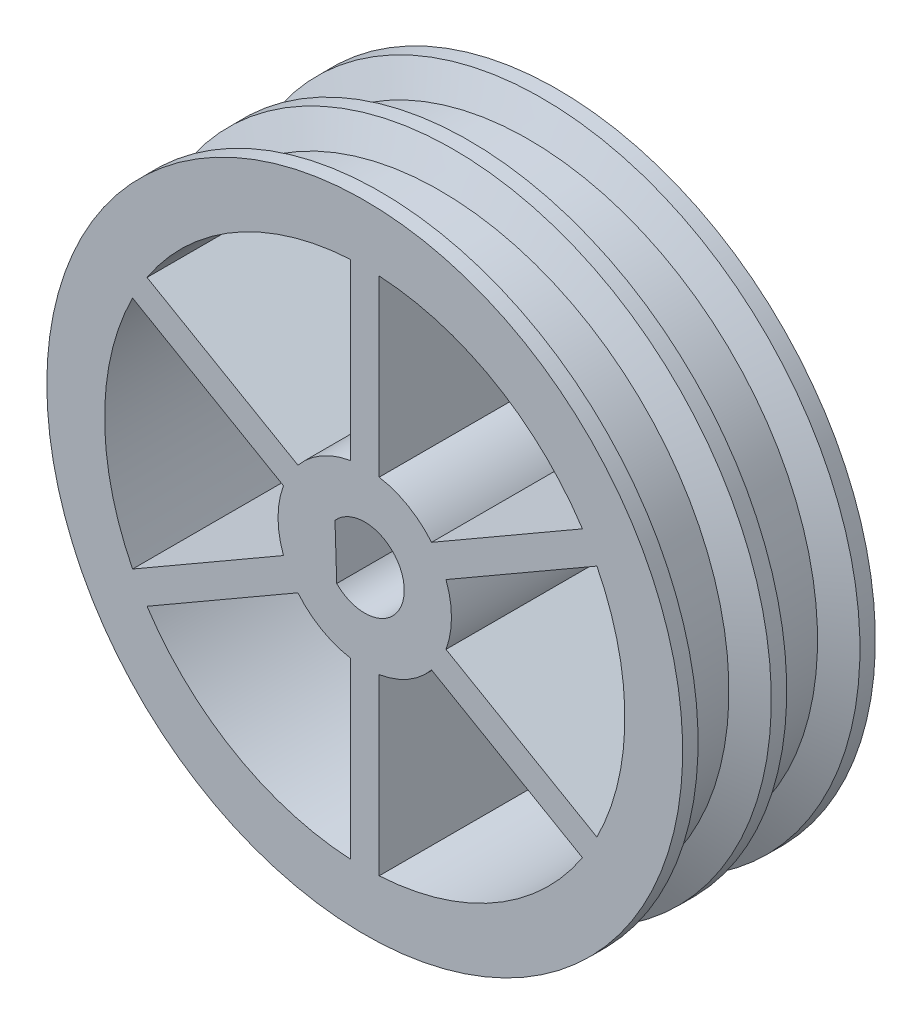
SolidWorks part; units mm, degrees
ref_plane "前视基准面" through (0, 0, 0) normal (0, 0, 1) x (1, 0, 0)
ref_plane "上视基准面" through (0, 0, 0) normal (0, 1, 0) x (1, 0, 0)
ref_plane "右视基准面" through (0, 0, 0) normal (1, 0, 0) x (0, 0, -1)
sketch "草图1" plane through (0, 0, 0) normal (0, 0, 1) x (1, 0, 0)
  line L0 (-3.0886, 2.6963) -> (-2.9082, -2.89)
  line L1 (0, 0) -> (0, 50000) construction
  line L2 (22.5966, 14.7782) -> (6.9352, 5.7361)
  line L4 (-1.5, 26.9583) -> (-1.5, 8.8741)
  line L6 (1.5, 26.9583) -> (1.5, 8.8741)
  line L7 (24.0966, 12.1801) -> (8.4352, 3.138)
  line L8 (24.0966, -12.1801) -> (8.4352, -3.138)
  line L9 (22.5966, -14.7782) -> (6.9352, -5.7361)
  line L10 (1.5, -26.9583) -> (1.5, -8.8741)
  line L11 (-1.5, -26.9583) -> (-1.5, -8.8741)
  line L12 (-22.5966, -14.7782) -> (-6.9352, -5.7361)
  line L13 (-24.0966, -12.1801) -> (-8.4352, -3.138)
  line L14 (-24.0966, 12.1801) -> (-8.4352, 3.138)
  line L15 (-22.5966, 14.7782) -> (-6.9352, 5.7361)
  arc A0 (-2.9082, -2.89) -> (-3.0886, 2.6963) centre (0, 0) ccw
  arc A1 (-8.4352, 3.138) -> (-8.4352, -3.138) centre (0, 0) ccw
  arc A2 (-24.0966, 12.1801) -> (-24.0966, -12.1801) centre (0, 0) ccw
  circle A3 centre (0, 0) radius 30
  arc A4 (-1.5, 8.8741) -> (-6.9352, 5.7361) centre (0, 0) ccw
  arc A5 (6.9352, 5.7361) -> (1.5, 8.8741) centre (0, 0) ccw
  arc A6 (22.5966, 14.7782) -> (1.5, 26.9583) centre (0, 0) ccw
  arc A7 (-1.5, 26.9583) -> (-22.5966, 14.7782) centre (0, 0) ccw
  arc A8 (-6.9352, -5.7361) -> (-1.5, -8.8741) centre (0, 0) ccw
  arc A9 (-22.5966, -14.7782) -> (-1.5, -26.9583) centre (0, 0) ccw
  arc A10 (8.4352, -3.138) -> (8.4352, 3.138) centre (0, 0) ccw
  arc A11 (24.0966, -12.1801) -> (24.0966, 12.1801) centre (0, 0) ccw
  arc A12 (1.5, -8.8741) -> (6.9352, -5.7361) centre (0, 0) ccw
  arc A13 (1.5, -26.9583) -> (22.5966, -14.7782) centre (0, 0) ccw
  point P35 (0, 0)
  dimension "D1" = 8.2
  dimension "D3" = 18
  dimension "D4" = 60
  dimension "D5" = 54
  dimension "D2" = 3
  dimension "D6" = 3
  dimension "D7" = 6
extrude "凸台-拉伸1" add sketch "草图1" along normal blind 20
ref_plane "基准面1" through (0, 0, 0) normal (-1, 0, 0) x (0, 0, 1)
sketch "草图2" plane through (0, 0, 0) normal (-1, 0, 0) x (0, 0, 1)
  line L0 (0, -30) -> (0, -33)
  line L1 (0, -33) -> (1.6, -33)
  line L2 (1.6, -33) -> (3, -30)
  line L3 (0, -30) -> (20, -30) construction
  line L4 (3, -30) -> (0, -30)
  line L5 (10, -30) -> (10, -45.7157) construction
  line L6 (17, -30) -> (20, -30)
  line L7 (18.4, -33) -> (17, -30)
  line L8 (20, -33) -> (18.4, -33)
  line L9 (20, -30) -> (20, -33)
  line L10 (7.8, -30) -> (9.2, -33)
  line L11 (9.2, -33) -> (10.8, -33)
  line L12 (7.8, -30) -> (12.2, -30)
  line L13 (0, 30) -> (0, -30) construction
  line L14 (20, -30) -> (20, 30) construction
  line L15 (12.2, -30) -> (10.8, -33)
  line L16 (0, 0) -> (50000, 0) construction
  point P24 (10, -33)
  point P25 (10, -30)
  dimension "D1" = 3
  dimension "D2" = 1.6
  dimension "D3" = 3
  dimension "D4" = 3
  dimension "D5" = 2.2
  dimension "D6" = 0.8
revolve "旋转1" add sketch "草图2" angle 360 about L16
